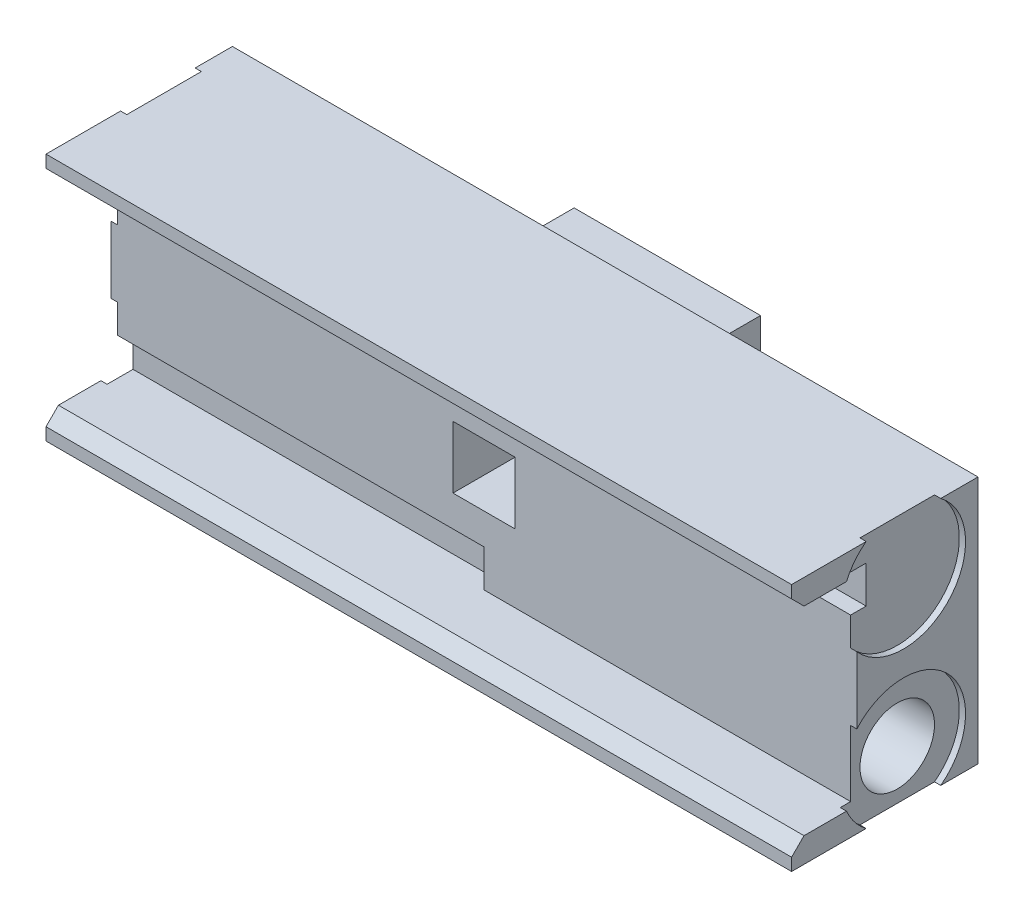
SolidWorks part; units mm, degrees
material "1060 Alloy"
ref_plane "Front Plane" through (0, 0, 0) normal (0, 0, 1) x (1, 0, 0)
ref_plane "Top Plane" through (0, 0, 0) normal (0, 1, 0) x (1, 0, 0)
ref_plane "Right Plane" through (0, 0, 0) normal (1, 0, 0) x (0, 0, -1)
sketch "Sketch1" plane through (0, 0, 0) normal (0, 0, 1) x (1, 0, 0)
  line L1 (-60, -20) -> (60, -20)
  line L2 (-60, -20) -> (-60, 20)
  line L3 (-60, 20) -> (60, 20)
  line L4 (60, -20) -> (60, 20)
  line L5 (-60, -20) -> (60, 20) construction
  line L6 (-60, 20) -> (60, -20) construction
  point P0 (0, 0)
  dimension "D1" = 120
  dimension "D2" = 40
extrude "Boss-Extrude1" add sketch "Sketch1" along normal blind 30
sketch "Sketch2" plane through (60, 0, 0) normal (1, 0, 0) x (0, 0, -1)
  line L0 (-30, -20) -> (0, -20) construction
  line L1 (-30, 16) -> (-19.7821, 16)
  line L2 (-30, 16) -> (-30, -16)
  line L3 (-30, -16) -> (-19.5, -16)
  line L4 (-19.5, 10) -> (-19.5, -16)
  line L5 (-19.7821, 16) -> (-17, 16)
  line L7 (-19.5, 10) -> (-17, 10)
  line L8 (-17, 16) -> (-17, 10)
  line L9 (-30, 20) -> (0, 20) construction
  line L10 (-30, -20) -> (-30, 20) construction
  dimension "D1" = 4
  dimension "D2" = 2.5
  dimension "D3" = 6
  dimension "D4" = 13
  dimension "D5" = 4
extrude "Cut-Extrude1" cut sketch "Sketch2" against normal blind 60
sketch "Sketch3" plane through (-60, 0, 0) normal (-1, 0, 0) x (0, 0, 1)
  line L0 (30, 20) -> (30, -20) construction
  line L1 (30, 16) -> (19.5, 16)
  line L2 (30, 16) -> (30, -16)
  line L3 (30, -16) -> (18.437, -16)
  line L4 (19.5, 16) -> (19.5, -10)
  line L5 (30, 20) -> (0, 20) construction
  line L6 (18.437, -16) -> (17, -16)
  line L8 (19.5, -10) -> (17, -10)
  line L9 (17, -16) -> (17, -10)
  line L10 (30, -20) -> (0, -20) construction
  dimension "D1" = 4
  dimension "D2" = 4
  dimension "D3" = 13
  dimension "D4" = 2.5
  dimension "D5" = 6
extrude "Cut-Extrude2" cut sketch "Sketch3" against normal blind 60
sketch "Sketch4" plane through (0, 0, 0) normal (0, 0, -1) x (-1, 0, 0)
  line L1 (-15, -15) -> (15, -15)
  line L2 (-15, -15) -> (-15, 15)
  line L3 (-15, 15) -> (15, 15)
  line L4 (15, -15) -> (15, 15)
  line L5 (-15, -15) -> (15, 15) construction
  line L6 (-15, 15) -> (15, -15) construction
  point P0 (0, 0)
  dimension "D1" = 30
  dimension "D2" = 30
extrude "Boss-Extrude2" add sketch "Sketch4" along normal blind 10
sketch "Sketch5" plane through (60, 0, 0) normal (1, 0, 0) x (0, 0, -1)
  line L0 (0, 0) -> (-12, 0) construction
  line L1 (-12, -12) -> (-12, 12) construction
  circle A0 centre (-12, 12) radius 10
  circle A1 centre (-12, -12) radius 10
  point P5 (-12, 0)
  dimension "D3" = 20
  dimension "D4" = 20
  dimension "D1" = 12
  dimension "D2" = 24
extrude "Cut-Extrude3" cut sketch "Sketch5" against normal blind 1
sketch "Sketch7" plane through (59, 0, 0) normal (1, 0, 0) x (0, 0, -1)
  circle A0 centre (-12, -12) radius 6
  dimension "D1" = 12
extrude "Cut-Extrude5" cut sketch "Sketch7" against normal blind 55
mirror "Mirror1" about plane through (0, 0, 0) normal (1, 0, 0) of "Cut-Extrude3"
sketch "Sketch6" plane through (0, 0, 19.5) normal (0, 0, 1) x (1, 0, 0)
  line L5 (-5, -5) -> (5, -5)
  line L6 (-5, -5) -> (-5, 5)
  line L7 (-5, 5) -> (5, 5)
  line L8 (5, -5) -> (5, 5)
  line L9 (-5, -5) -> (5, 5) construction
  line L10 (-5, 5) -> (5, -5) construction
  point P2 (0, 0)
  dimension "D1" = 10
  dimension "D2" = 10
extrude "Cut-Extrude4" cut sketch "Sketch6" against normal blind 10
chamfer "Chamfer1" distance 2 angle 45 2 edges at (0, 16, 30) (0, -16, 30)
sketch "Sketch8" plane through (-59, 0, 0) normal (-1, 0, 0) x (0, 0, 1)
  circle A0 centre (12, 12) radius 6
  dimension "D1" = 12
extrude "Cut-Extrude6" cut sketch "Sketch8" against normal blind 55
